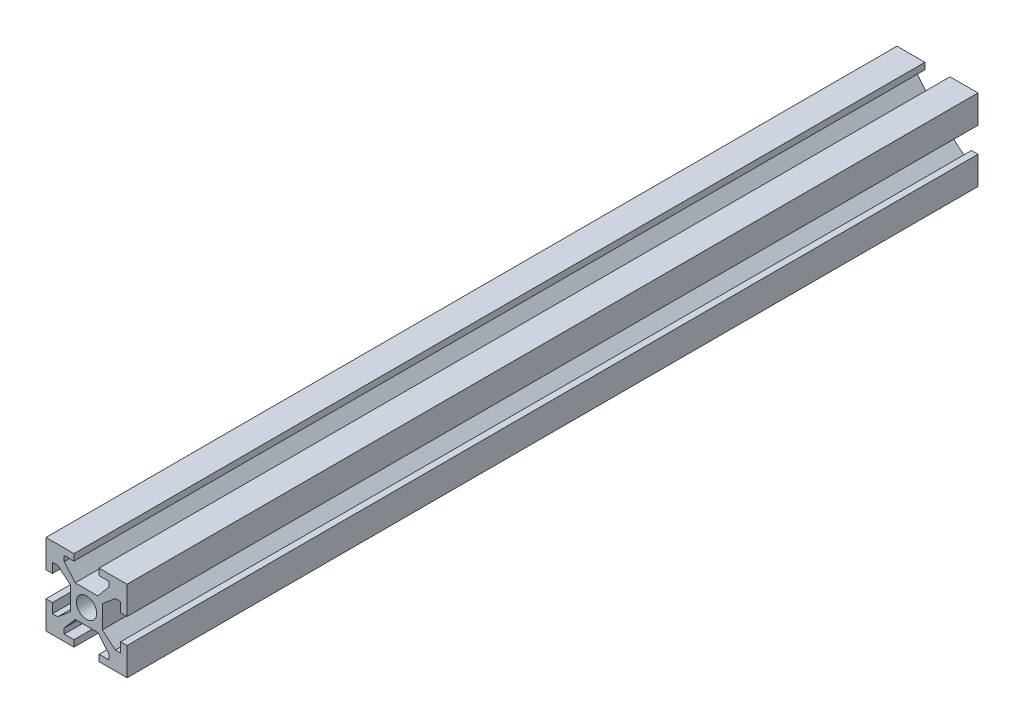
SolidWorks part; units mm, degrees
ref_plane "前视基准面" through (0, 0, 0) normal (0, 0, 1) x (1, 0, 0)
ref_plane "上视基准面" through (0, 0, 0) normal (0, 1, 0) x (1, 0, 0)
ref_plane "右视基准面" through (0, 0, 0) normal (1, 0, 0) x (0, 0, -1)
sketch "草图1" plane through (0, 0, 0) normal (0, 0, 1) x (1, 0, 0)
  line L0 (-10, 20) -> (-10, 0) construction
  line L1 (-20, 20) -> (-13.1, 20)
  line L2 (-20, 20) -> (-20, 13.1)
  line L3 (-20, 0) -> (-13.1, 0)
  line L4 (0, 20) -> (0, 13.1)
  line L5 (-20, 10) -> (0, 10) construction
  line L6 (-13.1, 20) -> (-13.1, 18.4)
  line L7 (-13.1, 18.4) -> (-15.5, 18.4)
  line L8 (-15.5, 18.4) -> (-15.5, 17.1043)
  line L9 (-15.5, 17.1043) -> (-12.797, 13.9)
  line L10 (-12.797, 13.9) -> (-7.203, 13.9)
  line L11 (-4.5, 17.1043) -> (-7.203, 13.9)
  line L12 (-4.5, 18.4) -> (-4.5, 17.1043)
  line L13 (-6.9, 20) -> (-6.9, 18.4)
  line L14 (-6.9, 18.4) -> (-4.5, 18.4)
  line L15 (-1.6, 13.1) -> (-1.6, 15.5)
  line L16 (-1.6, 15.5) -> (-2.8957, 15.5)
  line L17 (-2.8957, 15.5) -> (-6.1, 12.797)
  line L18 (-6.1, 12.797) -> (-6.1, 7.203)
  line L19 (-2.8957, 4.5) -> (-6.1, 7.203)
  line L20 (-1.6, 4.5) -> (-2.8957, 4.5)
  line L21 (-1.6, 6.9) -> (-1.6, 4.5)
  line L22 (0, 6.9) -> (-1.6, 6.9)
  line L23 (0, 13.1) -> (-1.6, 13.1)
  line L24 (-6.9, 1.6) -> (-4.5, 1.6)
  line L25 (-4.5, 1.6) -> (-4.5, 2.8957)
  line L26 (-4.5, 2.8957) -> (-7.203, 6.1)
  line L27 (-7.203, 6.1) -> (-12.797, 6.1)
  line L28 (-15.5, 2.8957) -> (-12.797, 6.1)
  line L29 (-15.5, 1.6) -> (-15.5, 2.8957)
  line L30 (-13.1, 1.6) -> (-15.5, 1.6)
  line L31 (-13.1, 0) -> (-13.1, 1.6)
  line L32 (-6.9, 0) -> (-6.9, 1.6)
  line L33 (-18.4, 6.9) -> (-18.4, 4.5)
  line L34 (-18.4, 4.5) -> (-17.1043, 4.5)
  line L35 (-17.1043, 4.5) -> (-13.9, 7.203)
  line L36 (-13.9, 7.203) -> (-13.9, 12.797)
  line L37 (-17.1043, 15.5) -> (-13.9, 12.797)
  line L38 (-18.4, 15.5) -> (-17.1043, 15.5)
  line L39 (-18.4, 13.1) -> (-18.4, 15.5)
  line L40 (-20, 13.1) -> (-18.4, 13.1)
  line L41 (-20, 6.9) -> (-18.4, 6.9)
  line L42 (-6.9, 20) -> (0, 20)
  line L43 (0, 6.9) -> (0, 0)
  line L44 (-20, 6.9) -> (-20, 0)
  line L45 (-6.9, 0) -> (0, 0)
  circle A0 centre (-10, 10) radius 2.5
  point P18 (-10, 13.9)
  point P55 (-10, 10)
  dimension "D3" = 5
  dimension "D1" = 20
  dimension "D2" = 20
  dimension "D4" = 5.5
  dimension "D5" = 6.1
  dimension "D6" = 3.1
  dimension "D7" = 1.6
  dimension "D8" = 4
extrude "凸台-拉伸1" add sketch "草图1" along normal blind 210
